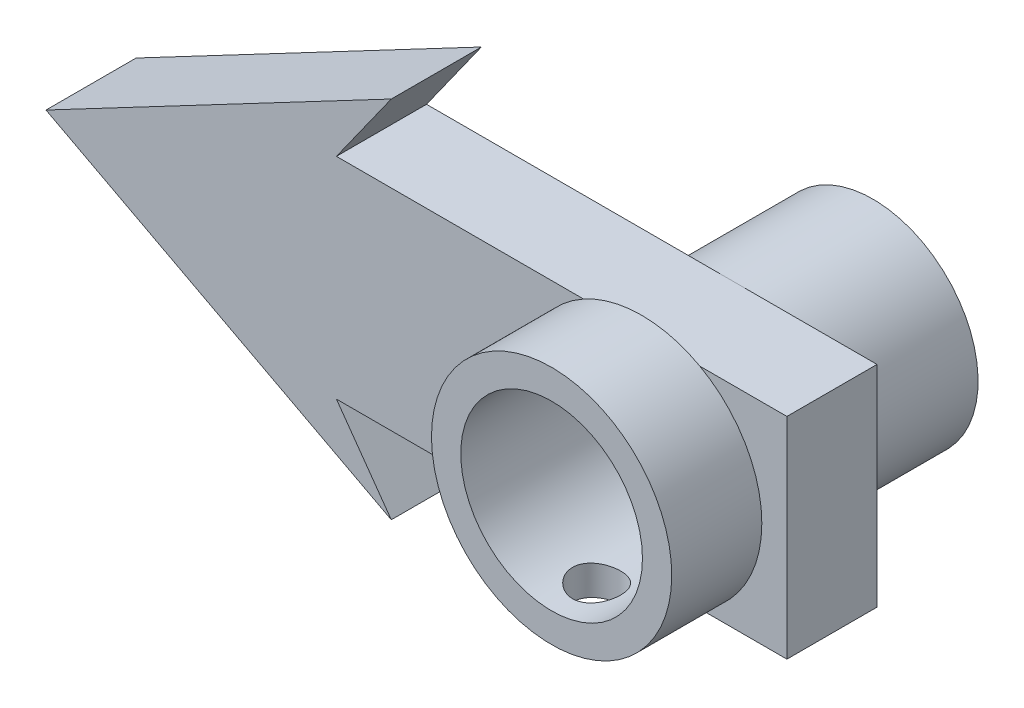
SolidWorks part; units mm, degrees
ref_plane "Front Plane" through (0, 0, 0) normal (0, 0, 1) x (1, 0, 0)
ref_plane "Top Plane" through (0, 0, 0) normal (0, 1, 0) x (1, 0, 0)
ref_plane "Right Plane" through (0, 0, 0) normal (1, 0, 0) x (0, 0, -1)
sketch "Sketch3" plane through (0, 0, 0) normal (0, 0, 1) x (1, 0, 0)
  line L0 (0, 0) -> (11.4976, 6.0667)
  line L1 (11.4976, 6.0667) -> (9.6701, 3.5)
  line L2 (9.6701, 3.5) -> (39.6701, 3.5)
  line L3 (39.6701, 3.5) -> (39.6701, -3.5)
  line L4 (3.3, 0) -> (-3.3, 0) construction
  line L5 (11.4976, -6.0667) -> (9.6701, -3.5)
  line L6 (9.6701, -3.5) -> (39.6701, -3.5)
  line L7 (0, 0) -> (11.4976, -6.0667)
  point P11 (39.6701, 0)
  dimension "D1" = 30
  dimension "D2" = 13
  dimension "D4" = 7
extrude "Boss-Extrude1" add sketch "Sketch3" along normal blind 3
sketch "Sketch8" plane through (0, 0, 3) normal (0, 0, 1) x (1, 0, 0)
  line L0 (0, 0) -> (39.6701, 0) construction
  line L1 (39.6701, -3.5) -> (39.6701, 3.5) construction
  circle A0 centre (19.835, 0) radius 4
  dimension "D1" = 8
extrude "Boss-Extrude4" add sketch "Sketch8" along normal blind 3
sketch "Sketch9" plane through (0, 0, 6) normal (0, 0, 1) x (1, 0, 0)
  circle A0 centre (19.835, 0) radius 3.025
  dimension "D1" = 6.05
extrude "Cut-Extrude5" cut sketch "Sketch9" against normal up to next
sketch "Sketch10" plane through (0, 0, 0) normal (0, 1, 0) x (1, 0, 0)
  line L0 (19.835, -3) -> (19.835, -6) construction
  line L1 (0, -3) -> (39.6701, -3) construction
  line L2 (16.81, -6) -> (22.86, -6) construction
  circle A0 centre (19.835, -4.5) radius 0.8
  dimension "D1" = 1.6
extrude "Cut-Extrude6" cut sketch "Sketch10" against normal up to next
sketch "Sketch11" plane through (0, 0, 0) normal (0, 0, -1) x (-1, 0, 0)
  line L0 (0, 0) -> (-39.6701, 0) construction
  circle A0 centre (-19.835, 0) radius 3.5
  dimension "D1" = 7
extrude "Boss-Extrude5" add sketch "Sketch11" along normal blind 4.7
sketch "Sketch12" plane through (0, 0, -4.7) normal (0, 0, -1) x (-1, 0, 0)
  circle A0 centre (-19.835, 0) radius 2
  dimension "D1" = 4
extrude "Cut-Extrude7" cut sketch "Sketch12" against normal blind 1.95
sketch "Sketch13" plane through (39.6701, 0, 0) normal (1, 0, 0) x (0, 0, -1)
  line L1 (-3, 3.5) -> (0, 3.5)
  line L2 (-3, 3.5) -> (-3, -3.5)
  line L3 (-3, -3.5) -> (0, -3.5)
  line L4 (0, 3.5) -> (0, -3.5)
extrude "Cut-Extrude8" cut sketch "Sketch13" against normal blind 15
